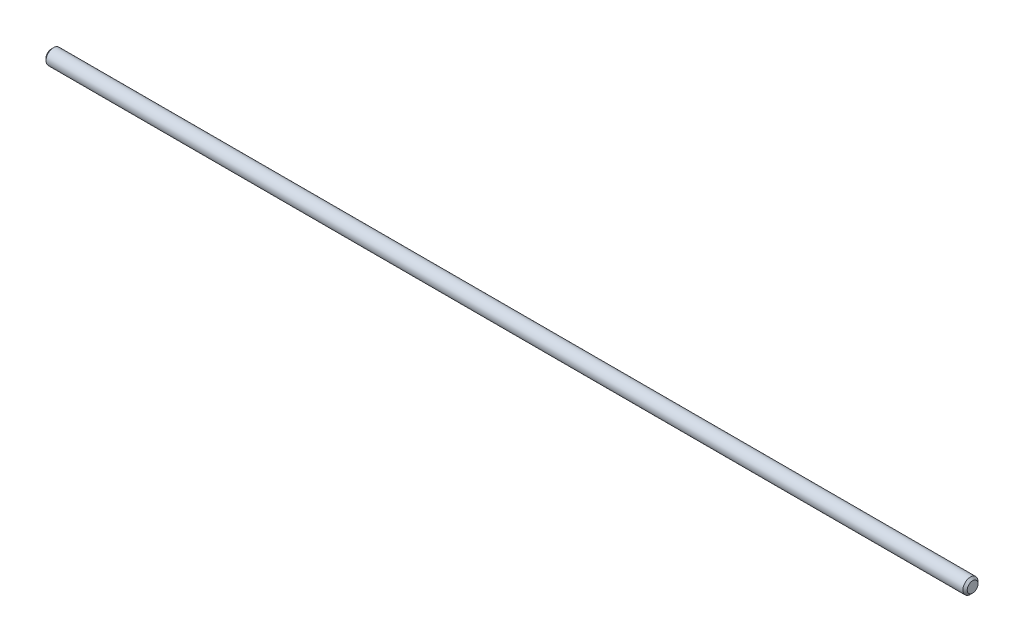
SolidWorks part; units mm, degrees
ref_plane "Front Plane" through (0, 0, 0) normal (0, 0, 1) x (1, 0, 0)
ref_plane "Top Plane" through (0, 0, 0) normal (0, 1, 0) x (1, 0, 0)
ref_plane "Right Plane" through (0, 0, 0) normal (1, 0, 0) x (0, 0, -1)
sketch "Sketch1" plane through (0, 0, 0) normal (0, 0, 1) x (1, 0, 0)
  line L0 (-101.6, 0) -> (101.6, 0) construction
  line L2 (-127, 2.0828) -> (-127, -2.0828) construction
  line L3 (-127, 0) -> (-126.2062, 0) construction
  line L4 (-127, 0) -> (127, 0) construction
  line L5 (101.6, 2.0828) -> (101.6, -2.0828) construction
  line L6 (-101.6, 2.0828) -> (-101.6, -2.0828) construction
  point P18 (-70.6438, 0)
  point P21 (-124.2219, -2.0828)
  dimension "Thread Diameter" = 4.1656
  dimension "Pitch" = 0.7937
  dimension "Length" = 254
  dimension "Segment Length" = 56.3562
  dimension "D1" = 203.2
  dimension "D2" = 2.7781
sketch "Sketch2" plane through (0, 0, 0) normal (1, 0, 0) x (0, 0, -1)
  line L0 (0, 2.0828) -> (0, -2.0828) construction
  line L1 (-2.0828, 0) -> (2.0828, 0) construction
  circle A0 centre (0, 0) radius 2.0828
extrude "Boss-Extrude1" add sketch "Sketch2" against normal up to vertex (127 mm away) and the other way up to vertex (127 mm away) up to point (-127, 0, 0) other way up to point (127, 0, 0)
chamfer "Chamfer1" distance 0.5953 angle 45 2 edges at (-127, 0, -2.0828) (127, 0, -2.0828)
equation "\"D1@Chamfer1\" = \"Pitch@Sketch1\" * .75"
equation "\"Segment Length@Sketch1\"=71*\"Pitch@Sketch1\""
equation "\"D1@Sketch1\"=\"Length@Sketch1\"*.8"
equation "\"D2@Sketch1\"=\"Pitch@Sketch1\"*3.50"
